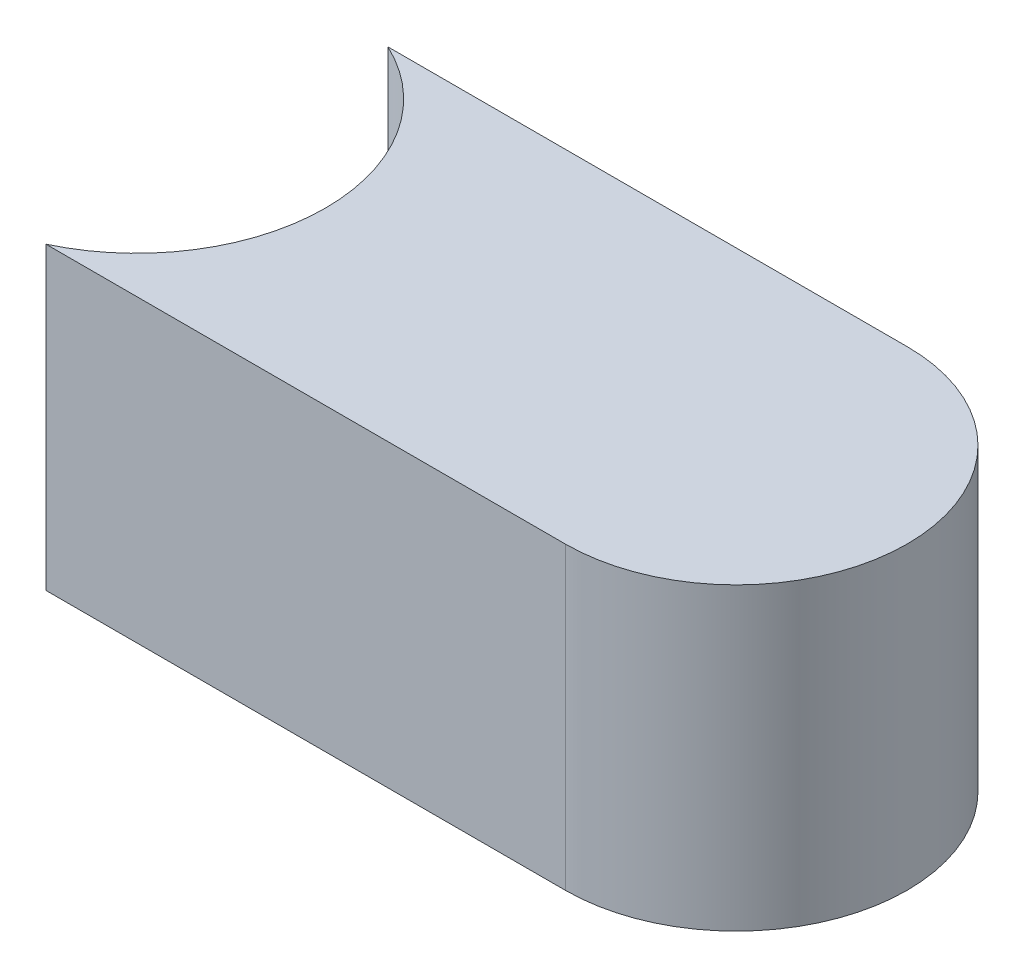
SolidWorks part; units mm, degrees
ref_plane "Front Plane" through (0, 0, 0) normal (0, 0, 1) x (1, 0, 0)
ref_plane "Top Plane" through (0, 0, 0) normal (0, 1, 0) x (1, 0, 0)
ref_plane "Right Plane" through (0, 0, 0) normal (1, 0, 0) x (0, 0, -1)
sketch "Sketch1" plane through (0, 0, 0) normal (0, 1, 0) x (1, 0, 0)
  line L0 (0.0261, 0) -> (13.0261, 0) construction
  line L1 (3.0261, 3) -> (13.0261, 3)
  line L2 (3.0261, -3) -> (13.0321, -3)
  line L3 (16.0261, 0.003) -> (6.0261, 0)
  line L4 (4.3678, 2.85) -> (13.0261, 2.85)
  line L5 (4.3678, -2.85) -> (13.0319, -2.85)
  arc A1 (13.0321, -3) -> (13.0261, 3) centre (13.0261, 0) ccw
  arc A2 (3.0261, -3) -> (3.0261, 3) centre (3.0261, 0) ccw
  arc A3 (13.0319, -2.85) -> (13.0261, 2.85) centre (13.0261, 0) ccw
  arc A4 (4.3678, -2.85) -> (4.3678, 2.85) centre (3.0261, 0) ccw
  point P2 (6.5, 0)
  dimension "D1" = 3
  dimension "D2" = 13
  dimension "D3" = 0.15
extrude "Boss-Extrude1" add sketch "Sketch1" along normal blind 5 contours L4 A3 L5 A4
